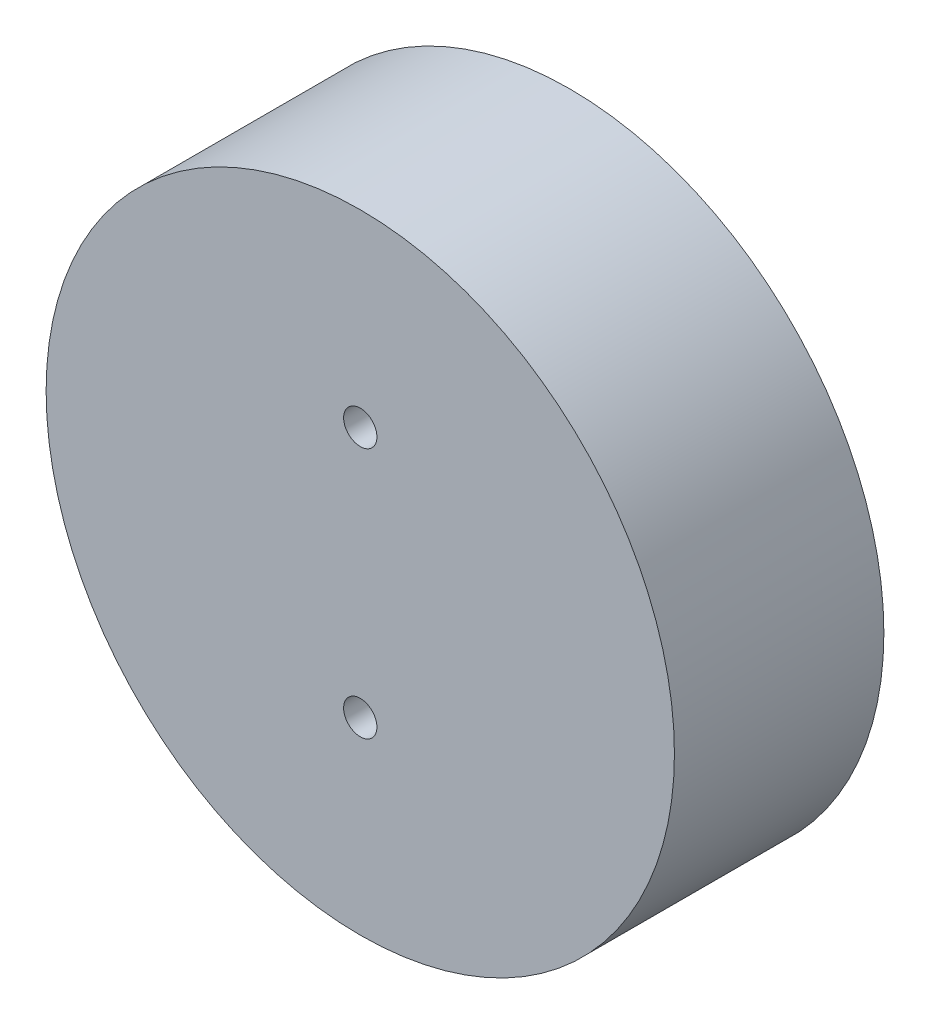
SolidWorks part; units mm, degrees
material "6061 Alloy"
ref_plane "Front Plane" through (0, 0, 0) normal (0, 0, 1) x (1, 0, 0)
ref_plane "Top Plane" through (0, 0, 0) normal (0, 1, 0) x (1, 0, 0)
ref_plane "Right Plane" through (0, 0, 0) normal (1, 0, 0) x (0, 0, -1)
sketch "Sketch1" plane through (0, 0, 0) normal (1, 0, 0) x (0, 0, -1)
  line L0 (0, 0) -> (51.2048, 0) construction
  line L1 (0, 38.1) -> (25.4, 38.1)
  line L2 (25.4, 38.1) -> (25.4, 30.48)
  line L3 (25.4, 30.48) -> (28.194, 30.48)
  line L4 (0, 38.1) -> (0, 0)
  line L5 (28.194, 30.48) -> (28.194, 0)
  line L6 (0, 0) -> (28.194, 0)
  dimension "D2" = 76.2
  dimension "D3" = 60.96
  dimension "D4" = 25.4
  dimension "D5" = 2.794
revolve "Revolve2" add sketch "Sketch1" angle 360 about L6
hole_wizard "#10-32 Tapped Hole1" positions "Sketch3" profile "Sketch2" tap size "#10-32" standard "Ansi Inch" end condition through all
sketch "Sketch3" plane through (0, 0, -28.194) normal (0, 0, -1) x (-1, 0, 0)
  point P0 (0, 15.24)
  point P1 (0, -15.24)
  dimension "D1" = 15.24
  dimension "D2" = 15.24
cosmetic thread "Hole Thread1" parameters "D2"=4.826
cosmetic thread "Hole Thread2" parameters "D2"=4.826
sketch "Sketch2" plane through (0, 15.24, -28.194) normal (1, 0, 0) x (0, 1, 0)
  line L0 (0, 0) -> (0, 28.194)
  line L1 (0, 28.194) -> (2.0193, 28.194)
  line L2 (2.0193, 28.194) -> (2.0193, 0)
  line L5 (2.0193, 0) -> (0, 0)
  line L11 (0, -6.35) -> (0, 107.95) construction
  dimension "Thru Tap Drill Dia." = 4.0386
  dimension "Thru Tap Drill Depth" = 28.194
hole_wizard "#10-32 Tapped Hole2" [suppressed] positions "Sketch5" profile "Sketch4" tap size "#10-32" standard "Ansi Inch"
sketch "Sketch5" plane through (0, 0, 0) normal (0, 0, 1) x (1, 0, 0)
  point P0 (15.24, 0)
  point P1 (-15.24, 0)
  dimension "D1" = 15.24
  dimension "D2" = 15.24
sketch "Sketch4" plane through (15.24, 0, 0) normal (1, 0, 0) x (0, -1, 0)
  line L0 (0, 0) -> (0, 13.2427)
  line L1 (0, 13.2427) -> (2.0193, 12.0294)
  line L2 (2.0193, 12.0294) -> (2.0193, 0)
  line L5 (2.0193, 0) -> (0, 0)
  line L10 (0, 13.2427) -> (-2.0193, 12.0294) construction
  line L11 (0, -6.35) -> (0, 107.95) construction
  dimension "Tap Drill Dia." = 4.0386
  dimension "Tap Drill Depth" = 12.0294
  dimension "Drill Angle" = 118
cosmetic thread "Hole Thread3" [suppressed] parameters "D1"=9.652, "D2"=4.826
cosmetic thread "Hole Thread4" [suppressed] parameters "D1"=9.652, "D2"=4.826
sketch "Sketch6" plane through (0, 0, -28.194) normal (0, 0, -1) x (-1, 0, 0)
  circle A0 centre (0, 0) radius 6.35
  dimension "D1" = 12.7
